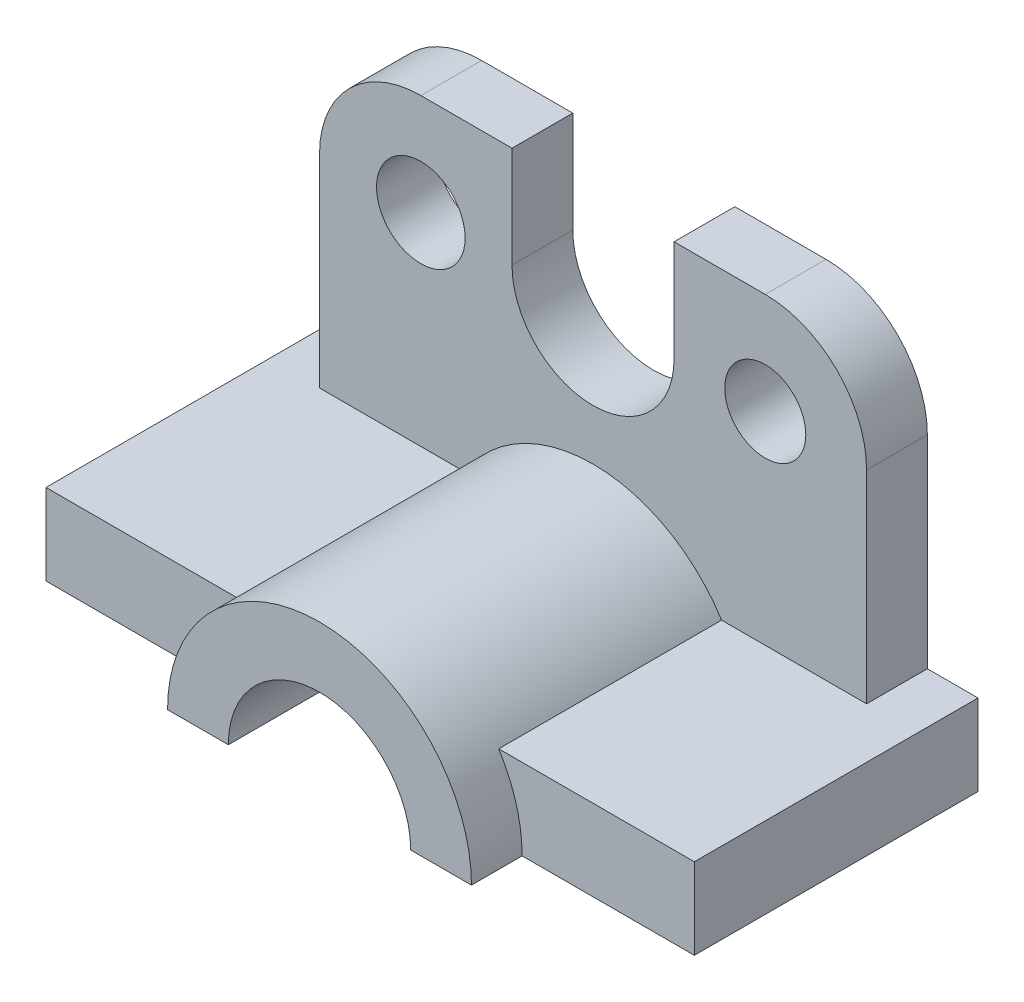
SolidWorks part; units mm, degrees
ref_plane "前视基准面" through (0, 0, 0) normal (0, 0, 1) x (1, 0, 0)
ref_plane "上视基准面" through (0, 0, 0) normal (0, 1, 0) x (1, 0, 0)
ref_plane "右视基准面" through (0, 0, 0) normal (1, 0, 0) x (0, 0, -1)
sketch "草图1" plane through (0, 0, 0) normal (0, 1, 0) x (1, 0, 0)
  line L1 (-32, 14) -> (32, 14)
  line L2 (-32, 14) -> (-32, -14)
  line L3 (-32, -14) -> (32, -14)
  line L4 (32, 14) -> (32, -14)
  line L5 (-32, 14) -> (32, -14) construction
  line L6 (-32, -14) -> (32, 14) construction
  point P0 (0, 0)
  dimension "D1" = 64
  dimension "D2" = 28
extrude "凸台-拉伸1" add sketch "草图1" along normal blind 8
sketch "草图2" plane through (0, 0, 0) normal (0, 1, 0) x (1, 0, 0)
  line L0 (32, 14) -> (-32, 14) construction
  line L1 (-27, 14) -> (27, 14)
  line L2 (-27, 14) -> (-27, 8)
  line L3 (-27, 8) -> (27, 8)
  line L4 (27, 14) -> (27, 8)
extrude "凸台-拉伸2" add sketch "草图2" along normal blind 38
fillet "圆角1" radius 10 2 edges at (27, 38, -11) (-27, 38, -11)
sketch "草图3" plane through (0, 0, 0) normal (0, 0, 1) x (1, 0, 0)
  line L0 (-32, 0) -> (32, 0) construction
  line L1 (-15, 0) -> (15, 0)
  arc A0 (15, 0) -> (-15, 0) centre (0, 0) ccw
extrude "凸台-拉伸3" add sketch "草图3" along normal blind 19 and the other way blind 13
sketch "草图4" plane through (0, 0, 0) normal (0, 0, 1) x (1, 0, 0)
  line L0 (-15, 0) -> (15, 0) construction
  line L1 (-9, 0) -> (9, 0)
  arc A0 (9, 0) -> (-9, 0) centre (0, 0) ccw
extrude "切除-拉伸1" cut sketch "草图4" against normal blind 21 and the other way blind 21
sketch "草图5" plane through (0, 0, 0) normal (0, 0, 1) x (1, 0, 0)
  line L0 (-8, 28) -> (-8, 38)
  line L1 (-17, 38) -> (17, 38) construction
  line L2 (8, 28) -> (8, 38)
  line L3 (-8, 38) -> (8, 38)
  arc A0 (-8, 28) -> (8, 28) centre (0, 28) ccw
  circle A1 centre (-17, 28) radius 4.3723
  circle A2 centre (17, 28) radius 4
extrude "切除-拉伸3" cut sketch "草图5" against normal blind 100
